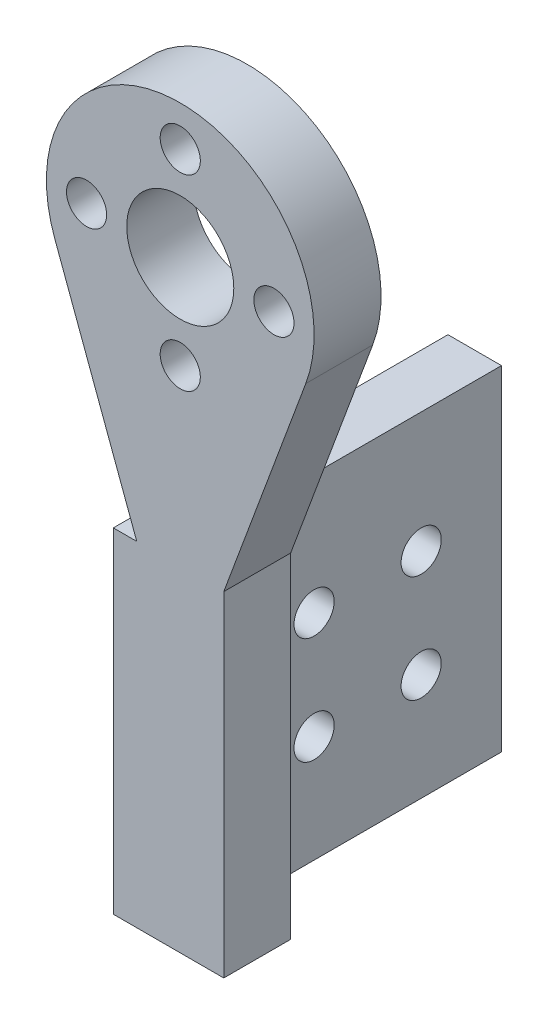
SolidWorks part; units mm, degrees
ref_plane "前视基准面" through (0, 0, 0) normal (0, 0, 1) x (1, 0, 0)
ref_plane "上视基准面" through (0, 0, 0) normal (0, 1, 0) x (1, 0, 0)
ref_plane "右视基准面" through (0, 0, 0) normal (1, 0, 0) x (0, 0, -1)
sketch "草图1" plane through (0, 0, 0) normal (0, 0, 1) x (1, 0, 0)
  line L0 (-3.5812, -8.028) -> (-3.5812, -12.6119)
  line L1 (-3.5812, 12.3881) -> (2.9188, 12.3881)
  line L2 (-3.5812, 12.3881) -> (-3.5812, -8.028)
  line L4 (2.9188, 12.3881) -> (2.9188, -6.6419)
  line L5 (-0.0812, -6.5) -> (-0.0812, 9.528) construction
  line L6 (-3.5812, 2.1801) -> (2.4188, 2.1801) construction
  line L7 (-3.5812, -12.6119) -> (2.9188, -12.6119)
  line L8 (2.9188, -12.6119) -> (2.9188, -6.6419)
  circle A0 centre (-0.0812, 8.2375) radius 1.25
  circle A1 centre (-0.0812, 2.7875) radius 1.25
  circle A2 centre (-0.0812, -2.6625) radius 1.25
  circle A3 centre (-0.0008, -8.1119) radius 1.25
  point P0 (0, 0)
  dimension "D3" = 2.5
  dimension "D4" = 2.5
  dimension "D5" = 2.5
  dimension "D1" = 2.5
  dimension "D2" = 4.5
  dimension "D6" = 5.45
  dimension "D7" = 6.5
  dimension "D8" = 5.45
  dimension "D9" = 5.45
  dimension "D10" = 3
  dimension "D11" = 25
extrude "凸台-拉伸1" add sketch "草图1" along normal blind 5
sketch "草图2" plane through (-3.5812, 0, 0) normal (-1, 0, 0) x (0, 0, 1)
  line L1 (0, 12.3881) -> (5, 12.3881)
  line L2 (0, 12.3881) -> (0, -12.6119)
  line L3 (0, -12.6119) -> (5, -12.6119)
  line L4 (5, 12.3881) -> (5, -12.6119)
extrude "凸台-拉伸2" add sketch "草图2" along normal blind 4
sketch "草图3" plane through (0, 0, 0) normal (0, 0, -1) x (-1, 0, 0)
  line L0 (-2.9188, 12.3881) -> (7.5812, 12.3881) construction
  line L1 (3.5812, 12.3881) -> (7.5812, 12.3881)
  line L2 (3.5812, 12.3881) -> (3.5812, -12.6119)
  line L3 (3.5812, -12.6119) -> (7.5812, -12.6119)
  line L4 (7.5812, 12.3881) -> (7.5812, -12.6119)
  line L5 (7.5812, 12.3881) -> (7.5812, -12.6119) construction
  line L6 (7.5812, -12.6119) -> (-2.9188, -12.6119) construction
  dimension "D1" = 4
extrude "凸台-拉伸3" add sketch "草图3" along normal blind 20 contours L2 L1 L4 L3
sketch "草图4" plane through (-3.5812, 0, 0) normal (1, 0, 0) x (0, 0, -1)
  line L0 (-0.5142, -0.6119) -> (22.6758, -0.6119) construction
  line L1 (10, 9.3991) -> (10, -15.8743) construction
  line L2 (20, 12.3881) -> (0, 12.3881) construction
  circle A0 centre (6, 3.3881) radius 1.5
  circle A1 centre (14, 3.3881) radius 1.5
  circle A2 centre (14, -4.6119) radius 1.5
  circle A3 centre (6, -4.6119) radius 1.5
  dimension "D1" = 3
  dimension "D2" = 4
  dimension "D3" = 4
  dimension "D4" = 9
extrude "切除-拉伸1" cut sketch "草图4" against normal blind 20
sketch "草图7" plane through (0, 0, 5) normal (0, 0, 1) x (1, 0, 0)
  circle A0 centre (-0.0812, 8.2375) radius 1.25
  circle A1 centre (-0.0812, 2.7875) radius 1.25
  circle A2 centre (-0.0812, -2.6625) radius 1.25
  circle A3 centre (-0.0008, -8.1119) radius 1.25
extrude "凸台-拉伸4" add sketch "草图7" against normal blind 5
sketch "草图8" plane through (0, 0, 5) normal (0, 0, 1) x (1, 0, 0)
  line L4 (-9.7078, 28.9112) -> (-3.5812, 12.3881)
  line L5 (9.0454, 28.9113) -> (2.9188, 12.3881)
  line L11 (-3.5812, 12.3881) -> (2.9188, 12.3881)
  circle A2 centre (6.6688, 32.3881) radius 1.5
  circle A3 centre (-0.3313, 39.388) radius 1.5
  circle A4 centre (-7.3313, 32.388) radius 1.5
  circle A5 centre (-0.3313, 25.388) radius 1.5
  circle A6 centre (-0.3313, 32.388) radius 4
  arc A7 (-9.7078, 28.9112) -> (9.0454, 28.9113) centre (-0.3313, 32.388) cw
  line M15 (2.9188, 12.3881) -> (-7.5812, 12.3881)
extrude "凸台-拉伸5" add sketch "草图8" against normal blind 5 contours A7 L4 L5 A6 A5 A4 A3 A2 M15
sketch "草图14" plane through (2.9188, 0, 0) normal (1, 0, 0) x (0, 0, -1)
  line L1 (-5, -12.6119) -> (20, -12.6119)
  line L2 (-5, -12.6119) -> (-5, 12.3881)
  line L3 (-5, 12.3881) -> (20, 12.3881)
  line L4 (20, -12.6119) -> (20, 12.3881)
  circle A0 centre (6, 3.3881) radius 1.5
  circle A1 centre (14, 3.3881) radius 1.5
  circle A2 centre (14, -4.6119) radius 1.5
  circle A3 centre (6, -4.6119) radius 1.5
extrude "凸台-拉伸9" add sketch "草图14" along normal blind 4 contours L2 L1 L4 L3 | A0 | A3 | A2 | A1
sketch "草图15" plane through (0, 0, -20) normal (0, 0, -1) x (-1, 0, 0)
  line L1 (3.5812, 12.3881) -> (7.5812, 12.3881)
  line L2 (3.5812, 12.3881) -> (3.5812, -12.6119)
  line L3 (3.5812, -12.6119) -> (7.5812, -12.6119)
  line L4 (7.5812, 12.3881) -> (7.5812, -12.6119)
extrude "切除-拉伸2" cut sketch "草图15" against normal blind 100
sketch "草图19" plane through (0, 0, 0) normal (0, 0, -1) x (-1, 0, 0)
  line L0 (0.3313, 32.388) -> (0.3312, -12.6119)
  line L1 (3.5812, -12.6119) -> (-2.9188, -12.6119) construction
  line L2 (0.3312, 9.8881) -> (1.3312, 9.8881)
  line L3 (1.3312, 9.8881) -> (1.3312, -12.6119)
  line L4 (3.5812, 12.3881) -> (1.3312, 12.3881)
  line L5 (1.3312, 12.3881) -> (1.3312, 9.8881)
  line L6 (1.3312, -12.6119) -> (5.3312, -12.6119)
  line L7 (5.3312, -12.6119) -> (5.3312, 12.3881)
  line L8 (5.3312, 12.3881) -> (3.5812, 12.3881)
  line M3 (3.5812, -12.6119) -> (3.5812, 12.3881)
  line M8 (-2.9188, -12.6119) -> (3.5812, -12.6119)
extrude "凸台-拉伸10" add sketch "草图19" along normal blind 20 contours L7 L8 L6 M3 | L4 L5 L3 M8 M3
sketch "草图20" plane through (6.9188, 0, 0) normal (1, 0, 0) x (0, 0, -1)
  circle A0 centre (6, 3.3881) radius 1.5
  circle A1 centre (14, 3.3881) radius 1.5
  circle A2 centre (6, -4.6119) radius 1.5
  circle A3 centre (14, -4.6119) radius 1.5
extrude "切除-拉伸3" cut sketch "草图20" against normal blind 20
sketch "草图21" plane through (6.9188, 0, 0) normal (1, 0, 0) x (0, 0, -1)
  line L1 (-5, 12.3881) -> (20, 12.3881)
  line L2 (-5, 12.3881) -> (-5, -12.6119)
  line L3 (-5, -12.6119) -> (20, -12.6119)
  line L4 (20, 12.3881) -> (20, -12.6119)
extrude "切除-拉伸4" cut sketch "草图21" against normal blind 4
sketch "草图22" plane through (0, 0, 0) normal (0, 0, 1) x (1, 0, 0)
  line L1 (-5.3312, 12.3881) -> (-3.5812, 12.3881)
  line L2 (-5.3312, 12.3881) -> (-5.3312, -12.6119)
  line L3 (-5.3312, -12.6119) -> (-3.5812, -12.6119)
  line L4 (-3.5812, 12.3881) -> (-3.5812, -12.6119)
extrude "凸台-拉伸11" add sketch "草图22" along normal blind 5
